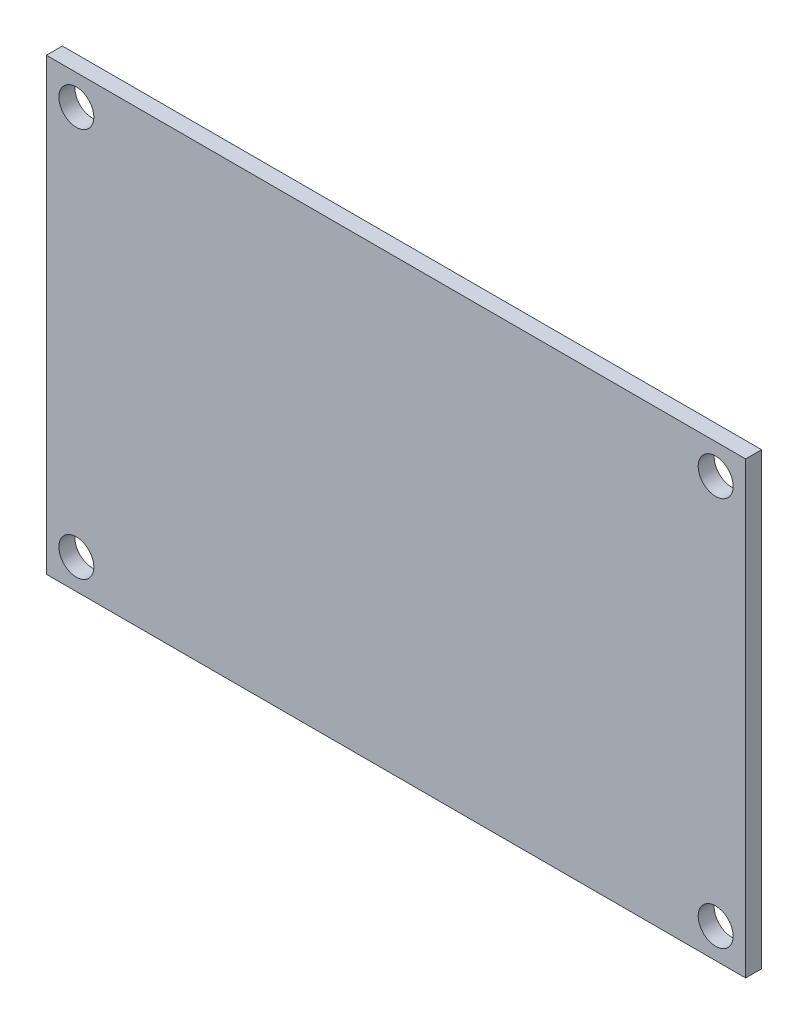
SolidWorks part; units mm, degrees
ref_plane "Front Plane" through (0, 0, 0) normal (0, 0, 1) x (1, 0, 0)
ref_plane "Top Plane" through (0, 0, 0) normal (0, 1, 0) x (1, 0, 0)
ref_plane "Right Plane" through (0, 0, 0) normal (1, 0, 0) x (0, 0, -1)
sketch "Sketch1" plane through (0, 0, 0) normal (0, 0, 1) x (1, 0, 0)
  line L1 (-35, -22.5) -> (35, -22.5)
  line L2 (-35, -22.5) -> (-35, 22.5)
  line L3 (-35, 22.5) -> (35, 22.5)
  line L4 (35, -22.5) -> (35, 22.5)
  line L5 (-35, -22.5) -> (35, 22.5) construction
  line L6 (-35, 22.5) -> (35, -22.5) construction
  point P0 (0, 0)
  dimension "D1" = 45
  dimension "D2" = 70
extrude "Boss-Extrude1" add sketch "Sketch1" along normal blind 1.6
sketch "Sketch2" plane through (0, 0, 1.6) normal (0, 0, 1) x (1, 0, 0)
  line L0 (0, 0) -> (0, 22.5) construction
  line L1 (0, 0) -> (-35, 0) construction
  line L2 (-35, 22.5) -> (-35, -22.5) construction
  line L3 (35, 22.5) -> (-35, 22.5) construction
  circle A0 centre (-32, 19.5) radius 1.75
  point P12 (-25.6152, 0)
  dimension "D3" = 3.5
  dimension "D1" = 64
  dimension "D2" = 39
extrude "Cut-Extrude1" cut sketch "Sketch2" against normal through all
mirror "Mirror1" about plane through (0, 0, 0) normal (0, 1, 0) of "Cut-Extrude1"
mirror "Mirror2" about plane through (0, 0, 0) normal (1, 0, 0) of "Mirror1", "Cut-Extrude1"
